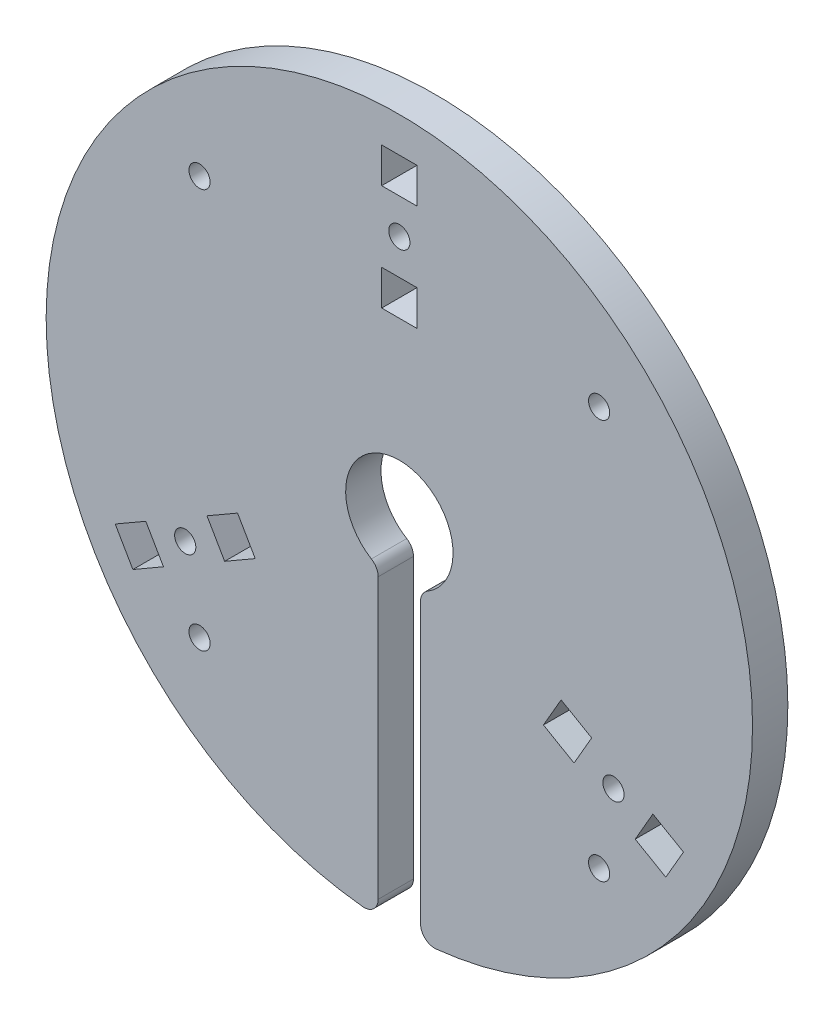
SolidWorks part; units mm, degrees
ref_plane "Plan de face" through (0, 0, 0) normal (0, 0, 1) x (1, 0, 0)
ref_plane "Plan de dessus" through (0, 0, 0) normal (0, 1, 0) x (1, 0, 0)
ref_plane "Plan de droite" through (0, 0, 0) normal (1, 0, 0) x (0, 0, -1)
sketch "Esquisse1" plane through (0, 0, 0) normal (0, 0, 1) x (1, 0, 0)
  line L0 (0, 0) -> (0, 31.2189) construction
  line L1 (0, 0) -> (37.7317, 0) construction
  line L2 (-3, 28.2406) -> (-3, -24.6241) construction
  line L3 (3, -24.6241) -> (3, 28.2406) construction
  line L4 (37.7317, 2.5) -> (-32.0453, 2.5) construction
  line L5 (-32.0453, -2.5) -> (37.7317, -2.5) construction
  line L6 (-3, -6.9828) -> (-3, -49.9099)
  line L7 (3, -49.9099) -> (3, -6.9828)
  line L8 (0, 0) -> (-43.3013, -25) construction
  line L9 (0, 0) -> (43.3013, -25) construction
  line L18 (0, 0) -> (32.7248, 32.7248) construction
  line L19 (0, 0) -> (-39.0036, 39.0036) construction
  circle A0 centre (0, 0) radius 7.6 construction
  circle A1 centre (0, 0) radius 50 construction
  arc A2 (-3, -6.9828) -> (3, -6.9828) centre (0, 0) cw
  arc A3 (-3, -49.9099) -> (3, -49.9099) centre (0, 0) cw
  circle A4 centre (0, 0) radius 35 construction
  circle A5 centre (0, 0) radius 40 construction
  circle A6 centre (28.2843, 28.2843) radius 1.5
  circle A7 centre (28.2843, -28.2843) radius 1.5
  circle A8 centre (-28.2843, 28.2843) radius 1.5
  circle A9 centre (-28.2843, -28.2843) radius 1.5
  line B0 (0, 30) -> (0, 40) construction
  line B1 (-2.5, 30) -> (-2.5, 25)
  line B2 (-2.5, 30) -> (2.5, 30)
  line B3 (2.5, 30) -> (2.5, 25)
  line B4 (-2.5, 25) -> (2.5, 25)
  line B5 (-2.5, 40) -> (-2.5, 45)
  line B6 (-2.5, 40) -> (2.5, 40)
  line B7 (2.5, 40) -> (2.5, 45)
  line B8 (-2.5, 45) -> (2.5, 45)
  circle B9 centre (0, 35) radius 1.5
  line B10 (-34.641, -20) -> (-25.9808, -15) construction
  line B11 (-35.891, -17.8349) -> (-40.2211, -20.3349)
  line B12 (-35.891, -17.8349) -> (-33.391, -22.1651)
  line B13 (-33.391, -22.1651) -> (-37.7211, -24.6651)
  line B14 (-40.2211, -20.3349) -> (-37.7211, -24.6651)
  line B15 (-27.2308, -12.8349) -> (-22.9006, -10.3349)
  line B16 (-27.2308, -12.8349) -> (-24.7308, -17.1651)
  line B17 (-24.7308, -17.1651) -> (-20.4006, -14.6651)
  line B18 (-22.9006, -10.3349) -> (-20.4006, -14.6651)
  circle B19 centre (-30.3109, -17.5) radius 1.5
  line B20 (25.9808, -15) -> (34.641, -20) construction
  line B21 (27.2308, -12.8349) -> (22.9006, -10.3349)
  line B22 (27.2308, -12.8349) -> (24.7308, -17.1651)
  line B23 (24.7308, -17.1651) -> (20.4006, -14.6651)
  line B24 (22.9006, -10.3349) -> (20.4006, -14.6651)
  line B25 (35.891, -17.8349) -> (40.2211, -20.3349)
  line B26 (35.891, -17.8349) -> (33.391, -22.1651)
  line B27 (33.391, -22.1651) -> (37.7211, -24.6651)
  line B28 (40.2211, -20.3349) -> (37.7211, -24.6651)
  circle B29 centre (30.3109, -17.5) radius 1.5
  dimension "D1" = 15.2
  dimension "D2" = 100
  dimension "D5" = 70
  dimension "D7" = 80
  dimension "D8" = 3
  dimension "D3" = 6
  dimension "D4" = 5
  dimension "D6" = 45
  dimension "D9" = 120
  dimension "D10" = 120
sketch_block_instance "Trou M3 plots 5mm-1"
sketch_block "Trou M3 plots 5mm" parameters "D2"=3, "D1"=5, "D3"=5, "D4"=10
sketch_block_instance "Trou M3 plots 5mm-2"
sketch_block_instance "Trou M3 plots 5mm-5"
extrude "Boss.-Extru.1" add sketch "Esquisse1" along normal blind 5
fillet "Fillet1" radius 2 4 edges at (-3, -6.9828, 2.5) (3, -6.9828, 2.5) (3, -49.9099, 2.5) (-3, -49.9099, 2.5)
